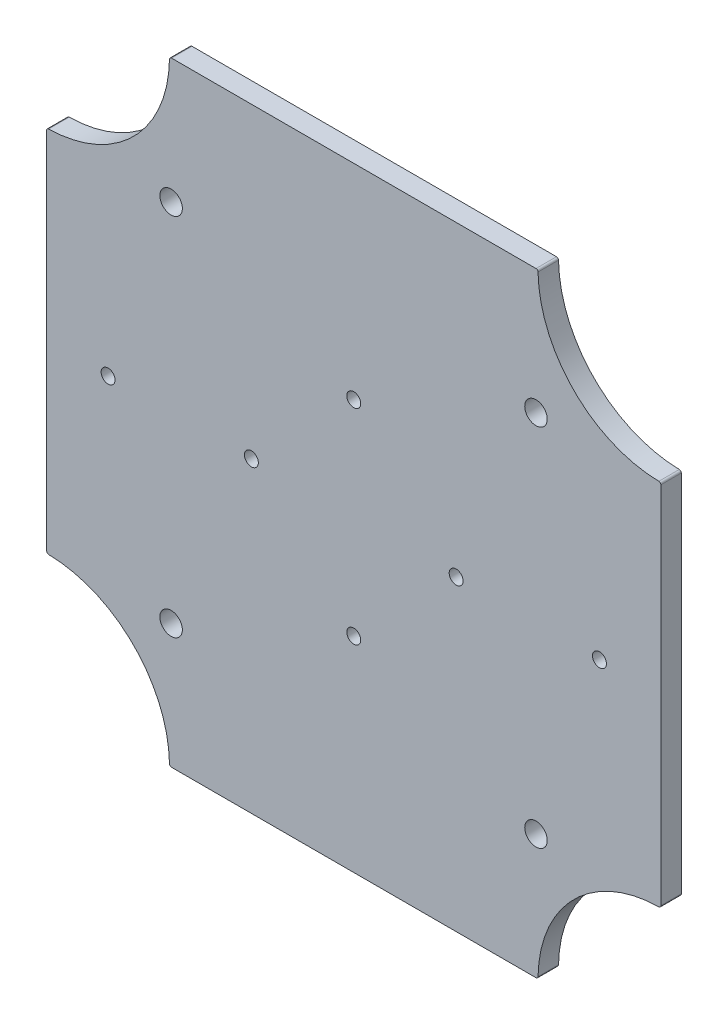
SolidWorks part; units mm, degrees
material "Plastique personnalisé"
ref_plane "Plan de face" through (0, 0, 0) normal (0, 0, 1) x (1, 0, 0)
ref_plane "Plan de dessus" through (0, 0, 0) normal (0, 1, 0) x (1, 0, 0)
ref_plane "Plan de droite" through (0, 0, 0) normal (1, 0, 0) x (0, 0, -1)
sketch "Esquisse1" plane through (0, 0, 0) normal (0, 0, 1) x (1, 0, 0)
  line L0 (75, 75) -> (-75, -75) construction
  line L1 (-75, 75) -> (75, 75)
  line L2 (-75, 75) -> (-75, -75)
  line L3 (-75, -75) -> (75, -75)
  line L4 (75, 75) -> (75, -75)
  line L5 (75, -75) -> (-75, 75) construction
  dimension "D1" = 150
  dimension "D2" = 150
extrude "Boss.-Extru.1" add sketch "Esquisse1" along normal blind 5
sketch "Esquisse2" plane through (0, 0, 5) normal (0, 0, 1) x (1, 0, 0)
  line L0 (75, 75) -> (-75, 75) construction
  line L1 (75, -75) -> (75, 75) construction
  line L2 (45, 75) -> (75, 75)
  line L3 (75, 75) -> (75, 45)
  line L4 (75, -75) -> (45, -75)
  line L5 (75, -45) -> (75, -75)
  line L6 (-75, -75) -> (-75, -45)
  line L7 (-45, -75) -> (-75, -75)
  line L8 (-75, 75) -> (-45, 75)
  line L9 (-75, 45) -> (-75, 75)
  arc A0 (45, 75) -> (75, 45) centre (75, 75) ccw
  arc A1 (75, -45) -> (45, -75) centre (75, -75) ccw
  arc A2 (-45, -75) -> (-75, -45) centre (-75, -75) ccw
  arc A3 (-75, 45) -> (-45, 75) centre (-75, 75) ccw
  point P20 (0, 0)
  point P21 (0, 0)
  dimension "D1" = 30
  dimension "D2" = 4
extrude "Enlèv. mat.-Extru.1" cut sketch "Esquisse2" against normal up to surface (5 mm away) up to face at (0, 0, 0)
hole_wizard "Dégagement M31" positions "Esquisse3" profile "Esquisse4" hole size "M3" standard "ISO" end condition up to next
sketch "Esquisse3" plane through (0, 0, 0) normal (0, 0, -1) x (-1, 0, 0)
  line L0 (-75, -45) -> (-75, 45) construction
  line L1 (75, 45) -> (75, -45) construction
  point P0 (0, 25)
  point P2 (0, -25)
  point P4 (60, 0)
  point P6 (25, 0)
  point P8 (-25, 0)
  point P10 (-60, 0)
  dimension "D1" = 25
  dimension "D2" = 25
  dimension "D3" = 25
  dimension "D4" = 25
  dimension "D5" = 15
  dimension "D6" = 15
sketch "Esquisse4" plane through (0, 25, 0) normal (1, 0, 0) x (0, 1, 0)
  line L0 (0, 0) -> (0, 5)
  line L1 (0, 5) -> (1.7, 5)
  line L2 (1.7, 5) -> (1.7, 0)
  line L5 (1.7, 0) -> (0, 0)
  line L11 (0, -6.35) -> (0, 107.95) construction
  dimension "Diamètre du perçage jusqu'au prochain" = 3.4
  dimension "Profondeur du perçage jusqu'au prochain" = 5
fillet "Congé1" radius 0.5 8 edges at (75, 45, 2.5) (45, 75, 2.5) (-45, 75, 2.5) (-75, 45, 2.5) (-75, -45, 2.5) (-45, -75, 2.5) (75, -45, 2.5) (45, -75, 2.5)
sketch "Esquisse6" plane through (0, 0, 0) normal (0, 0, -1) x (-1, 0, 0)
  line L0 (-44.5041, 75) -> (-44.5041, 44.5041) construction
  line L1 (-44.5041, 44.5041) -> (-75, 44.5041) construction
  line L2 (-75, -44.5041) -> (-75, 44.5041) construction
  line L3 (-75, 44.5041) -> (-44.5041, 75) construction
  circle A1 centre (-44.5041, 44.5041) radius 2.75
  dimension "D1" = 5.5
extrude "Enlèv. mat.-Extru.2" cut sketch "Esquisse6" against normal up to next contours A1
pattern_circular "Répétition circulaire1" count 4 over 360 about axis through (-0.054, -0.054, 0) along (0, 0, 1) of "Enlèv. mat.-Extru.2"
